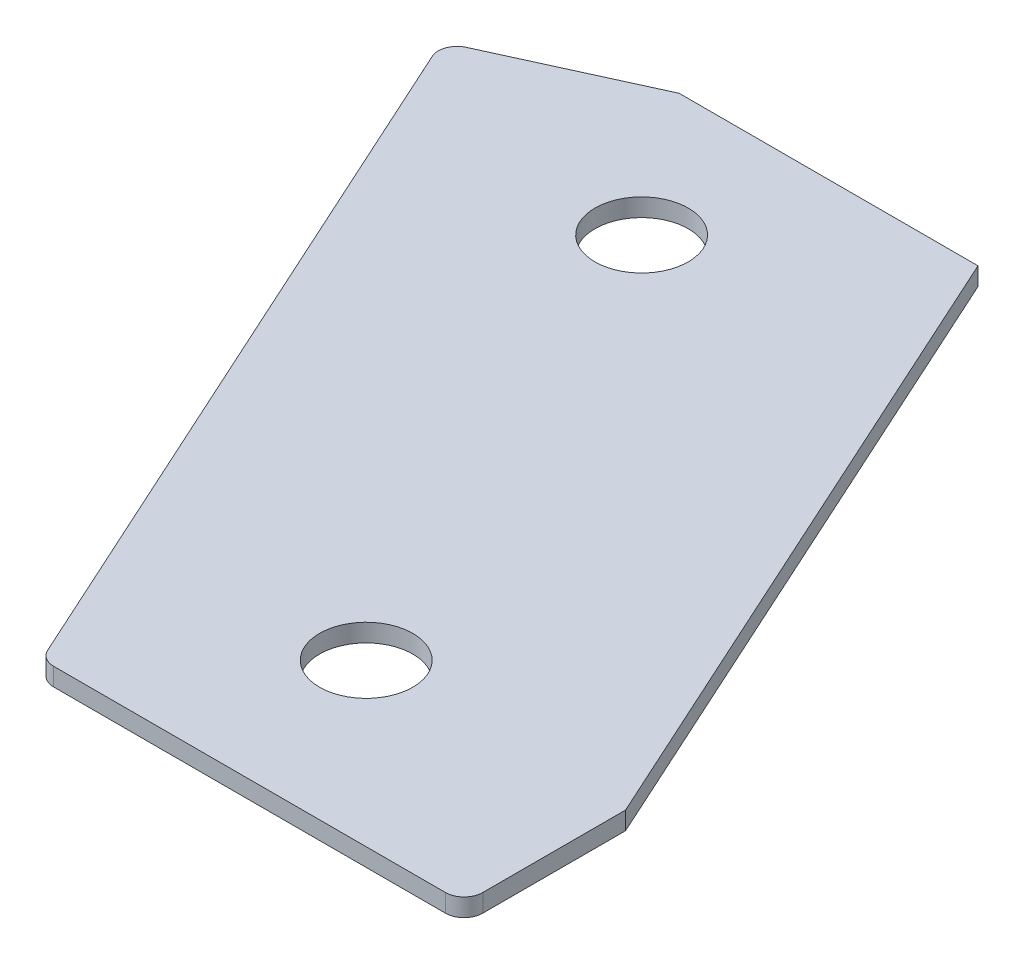
SolidWorks part; units mm, degrees
material "ASTM A36 Steel"
ref_plane "Front Plane" through (0, 0, 0) normal (0, 0, 1) x (1, 0, 0)
ref_plane "Top Plane" through (0, 0, 0) normal (0, 1, 0) x (1, 0, 0)
ref_plane "Right Plane" through (0, 0, 0) normal (1, 0, 0) x (0, 0, -1)
sketch "Sketch1" plane through (0, 0, 0) normal (0, 1, 0) x (1, 0, 0)
  line L0 (67.9451, -67.738) -> (67.9451, -107.538)
  line L1 (62.7451, -112.738) -> (-46.4315, -112.738)
  line L2 (-51.1633, -109.6944) -> (-140.9258, 87.2715)
  line L3 (-138.3504, 94.1597) -> (-97.5842, 112.738)
  line L4 (67.9451, -67.738) -> (-14.3025, 112.738)
  line L5 (-97.5842, 112.738) -> (-14.3025, 112.738)
  arc A0 (62.7451, -112.738) -> (67.9451, -107.538) centre (62.7451, -107.538) ccw
  arc A1 (-51.1633, -109.6944) -> (-46.4315, -112.738) centre (-46.4315, -107.538) ccw
  arc A2 (-138.3504, 94.1597) -> (-140.9258, 87.2715) centre (-136.194, 89.4279) ccw
extrude "Boss-Extrude1" add sketch "Sketch1" along normal blind 5
sketch "Sketch2" plane through (0, 5, 0) normal (0, 1, 0) x (1, 0, 0)
  line L0 (-46.4315, -112.738) -> (62.7451, -112.738) construction
  line L1 (-140.9258, 87.2715) -> (-51.1633, -109.6944) construction
  circle A0 centre (-4.3471, -67.738) radius 13
  circle A1 centre (-68.6245, 73.306) radius 13
  dimension "D1" = 26
  dimension "D2" = 45
  dimension "D3" = 60
  dimension "D4" = 26
  dimension "D5" = 155
  dimension "D6" = 60
extrude "Cut-Extrude1" cut sketch "Sketch2" against normal blind 5
